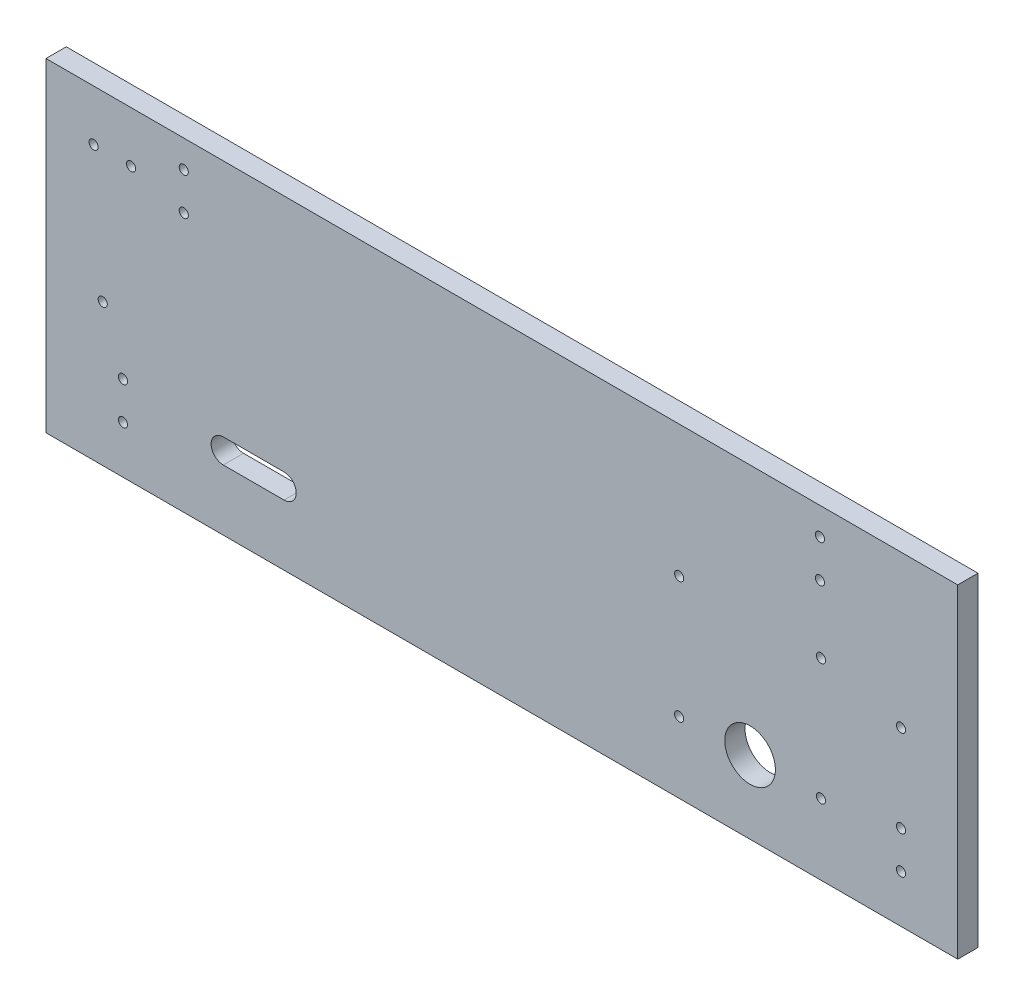
SolidWorks part; units mm, degrees
material "Multistrato di pioppo"
ref_plane "Piano frontale" through (0, 0, 0) normal (0, 0, 1) x (1, 0, 0)
ref_plane "Piano superiore" through (0, 0, 0) normal (0, 1, 0) x (1, 0, 0)
ref_plane "Piano destro" through (0, 0, 0) normal (1, 0, 0) x (0, 0, -1)
sketch "Schizzo1" plane through (0, 0, 0) normal (0, 0, 1) x (1, 0, 0)
  line L1 (0, 0) -> (450, 0)
  line L2 (0, 0) -> (0, 160)
  line L3 (0, 160) -> (450, 160)
  line L4 (450, 0) -> (450, 160)
  dimension "D1" = 450
  dimension "D2" = 160
extrude "Estrusione-Estrusione1" add sketch "Schizzo1" along normal blind 10
sketch "Schizzo2" plane through (0, 0, 10) normal (0, 0, 1) x (1, 0, 0)
  line L0 (102.5, 36) -> (347.5, 36) construction
  line L1 (225, 0) -> (225, 36) construction
  line L2 (0, 0) -> (450, 0) construction
  line L3 (87.5, 36) -> (117.5, 36) construction
  line L4 (87.5, 42) -> (117.5, 42)
  line L5 (87.5, 30) -> (117.5, 30)
  circle A1 centre (347.5, 36) radius 12.5
  arc A2 (87.5, 42) -> (87.5, 30) centre (87.5, 36) ccw
  arc A3 (117.5, 30) -> (117.5, 42) centre (117.5, 36) ccw
  circle A8 centre (382, 146.5) radius 2.25
  circle A9 centre (382, 128) radius 2.25
  circle A10 centre (68, 146.5) radius 2.25
  circle A11 centre (68, 128) radius 2.25
  circle A12 centre (38, 42) radius 2.25
  circle A13 centre (38, 23.5) radius 2.25
  circle A14 centre (422, 23.5) radius 2.25
  circle A15 centre (422, 42) radius 2.25
  circle A16 centre (23.5, 134.9337) radius 2.25
  circle A17 centre (42, 134.9337) radius 2.25
  circle A18 centre (28, 70) radius 2.25
  circle A19 centre (422, 85) radius 2.25
  circle A20 centre (312.5, 95) radius 2.25
  circle A21 centre (382.5, 95) radius 2.25
  circle A22 centre (382.5, 35) radius 2.25
  circle A23 centre (312.5, 35) radius 2.25
  point P9 (102.5, 36)
  dimension "D2" = 25
  dimension "D3" = 12
  dimension "D5" = 30
  dimension "D6" = 4.5
  dimension "D20" = 4.5
  dimension "D11" = 4.5
  dimension "D1" = 36
  dimension "D4" = 245
extrude "Taglio-Estrusione1" cut sketch "Schizzo2" against normal blind 10
